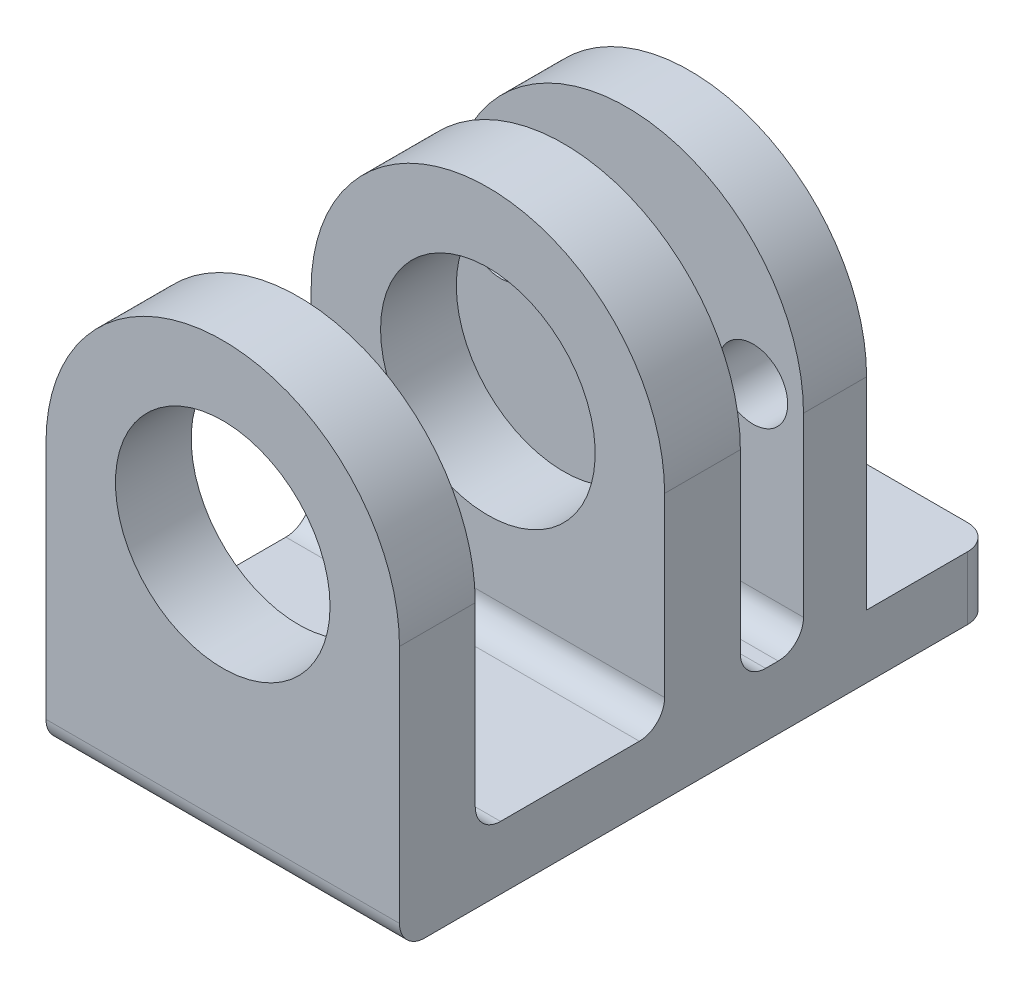
SolidWorks part; units mm, degrees
material "ABS"
ref_plane "Front Plane" through (0, 0, 0) normal (0, 0, 1) x (1, 0, 0)
ref_plane "Top Plane" through (0, 0, 0) normal (0, 1, 0) x (1, 0, 0)
ref_plane "Right Plane" through (0, 0, 0) normal (1, 0, 0) x (0, 0, -1)
sketch "Sketch1" plane through (0, 0, 0) normal (0, 0, 1) x (1, 0, 0)
  line L0 (-14, 0) -> (-14, -16)
  line L1 (-14, -16) -> (14, -16)
  line L2 (14, -16) -> (14, 0)
  circle A0 centre (0, 0) radius 8.5
  circle A1 centre (0, 0) radius 14
  dimension "D1" = 17
  dimension "D2" = 28
  dimension "D3" = 30
extrude "Boss-Extrude1" add sketch "Sketch1" along normal blind 6 contours A1 A0 | A1 L1 L2 | A1 L0 L1
ref_plane "Plane1" through (0, 0, -15) normal (0, 0, -1) x (-1, 0, 0)
sketch "Sketch2" plane through (0, 0, -15) normal (0, 0, -1) x (-1, 0, 0)
  line L0 (-14, -16) -> (-14, 0) construction
  line L1 (14, -16) -> (-14, -16) construction
  line L2 (14, 0) -> (14, -16) construction
  line L3 (-14, -16) -> (-14, 0)
  line L4 (14, -16) -> (-14, -16)
  line L5 (14, 0) -> (14, -16)
  arc A0 (14, 0) -> (-14, 0) centre (0, 0) ccw construction
  circle A1 centre (0, 0) radius 8.5 construction
  arc A2 (14, 0) -> (-14, 0) centre (0, 0) ccw
  circle A3 centre (0, 0) radius 8.5
extrude "Boss-Extrude2" add sketch "Sketch2" along normal blind 6 separate body
ref_plane "Plane2" through (0, 0, -26) normal (0, 0, -1) x (-1, 0, 0)
sketch "Sketch3" plane through (0, 0, -26) normal (0, 0, -1) x (-1, 0, 0)
  line L0 (-10, 0) -> (10, 0) construction
  line L3 (-14, -16) -> (14, -16)
  line L4 (14, -16) -> (14, 0)
  line L5 (-14, 0) -> (-14, -16)
  line L6 (-14, -16) -> (14, -16)
  line L7 (14, -16) -> (14, 0)
  line L8 (-14, 0) -> (-14, -16)
  circle A0 centre (0, 0) radius 5
  arc A1 (14, 0) -> (-14, 0) centre (0, 0) ccw
  arc A2 (14, 0) -> (-14, 0) centre (0, 0) ccw
  circle A3 centre (-10, 0) radius 2.75
  circle A4 centre (10, 0) radius 2.75
  point P8 (0, 0)
  dimension "D2" = 10
  dimension "D4" = 5.5
  dimension "D3" = 20
  dimension "D1" = 0
extrude "Boss-Extrude3" add sketch "Sketch3" along normal blind 5 separate body
sketch "Sketch4" plane through (0, 0, 6) normal (0, 0, 1) x (1, 0, 0)
  line L0 (14, -16) -> (14, 0) construction
  line L1 (-14, -16) -> (14, -16)
  line L2 (-14, -16) -> (-14, -21)
  line L3 (-14, -21) -> (14, -21)
  line L4 (14, -16) -> (14, -21)
  dimension "D1" = 5
extrude "Boss-Extrude5" add sketch "Sketch4" against normal offset from surface (47 mm away) 10 up to face at (7.25, 0, -31) offset beyond the face yes
fillet "Fillet1" radius 2 7 edges at (-14, -18.5, -41) (14, -18.5, -41) (0, -16, -26) (0, -16, -21) (0, -16, -15) (0, -21, 6) (0, -16, 0)
